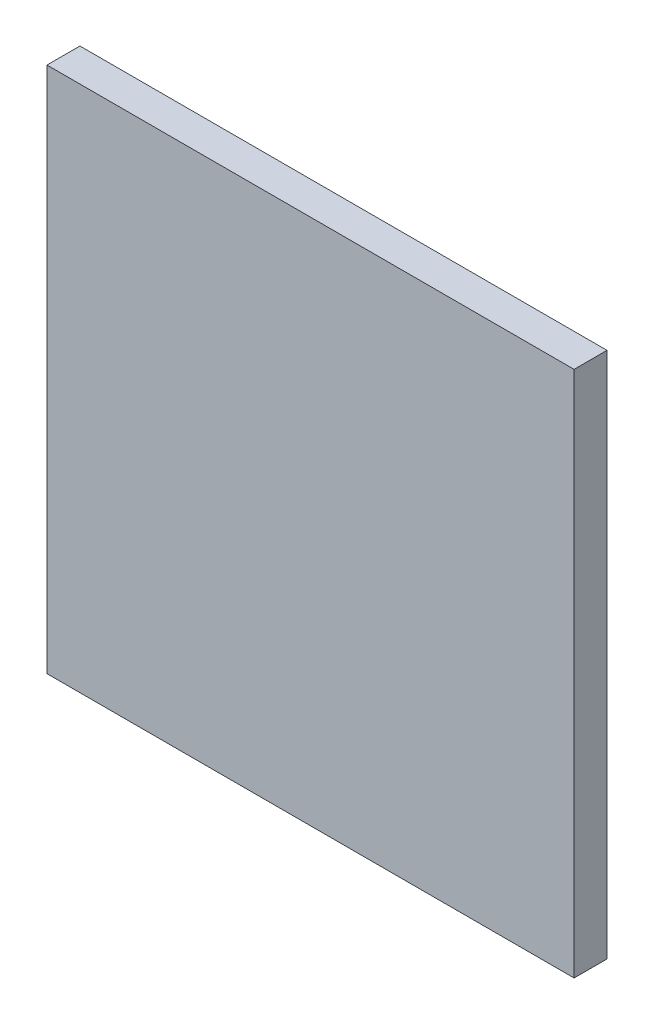
SolidWorks part; units mm, degrees
material "Стекло"
ref_plane "Спереди" through (0, 0, 0) normal (0, 0, 1) x (1, 0, 0)
ref_plane "Сверху" through (0, 0, 0) normal (0, 1, 0) x (1, 0, 0)
ref_plane "Справа" through (0, 0, 0) normal (1, 0, 0) x (0, 0, -1)
sketch "Эскиз1" plane through (0, 0, 0) normal (0, 0, 1) x (1, 0, 0)
  line L1 (-400, -400) -> (400, -400)
  line L2 (-400, -400) -> (-400, 400)
  line L3 (-400, 400) -> (400, 400)
  line L4 (400, -400) -> (400, 400)
  line L5 (-400, -400) -> (400, 400) construction
  line L6 (-400, 400) -> (400, -400) construction
  point P0 (0, 0)
  dimension "D1" = 800
extrude "Бобышка-Вытянуть1" add sketch "Эскиз1" along normal mid plane 50
